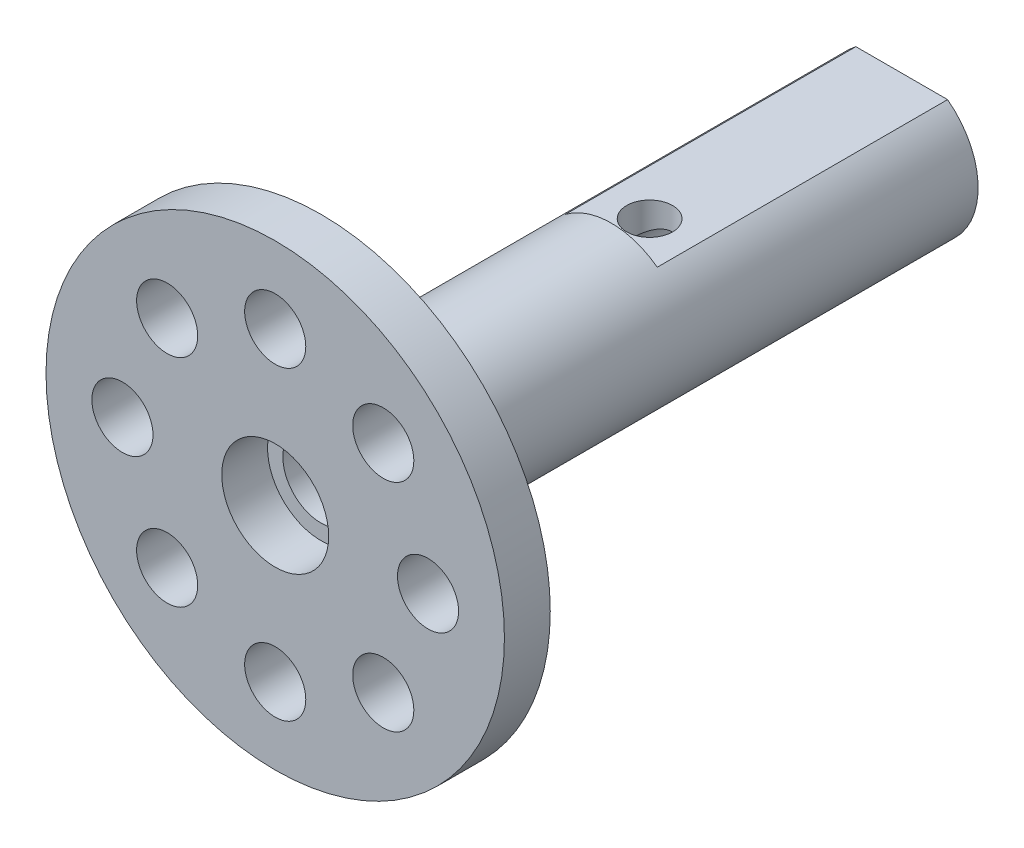
SolidWorks part; units mm, degrees
material "普通碳钢"
ref_plane "前视基准面" through (0, 0, 0) normal (0, 0, 1) x (1, 0, 0)
ref_plane "上视基准面" through (0, 0, 0) normal (0, 1, 0) x (1, 0, 0)
ref_plane "右视基准面" through (0, 0, 0) normal (1, 0, 0) x (0, 0, -1)
sketch "草图1" plane through (0, 0, 0) normal (0, 0, 1) x (1, 0, 0)
  circle A0 centre (0, 0) radius 5
  dimension "D1" = 10
extrude "凸台-拉伸1" add sketch "草图1" along normal blind 35
sketch "草图2" plane through (0, 0, 35) normal (0, 0, 1) x (1, 0, 0)
  circle A0 centre (0, 0) radius 6
  dimension "D1" = 12
extrude "凸台-拉伸2" add sketch "草图2" along normal blind 3
sketch "草图3" plane through (0, 0, 38) normal (0, 0, 1) x (1, 0, 0)
  line L0 (10, 0) -> (0, 0) construction
  line L1 (0, 0) -> (7.0711, 7.0711) construction
  circle A0 centre (0, 0) radius 15
  circle A1 centre (0, 0) radius 10 construction
  circle A2 centre (0, 10) radius 2
  circle A3 centre (10, 0) radius 2
  circle A4 centre (0, -10) radius 2
  circle A5 centre (-10, 0) radius 2
  circle A6 centre (7.0711, 7.0711) radius 2
  circle A7 centre (7.0711, -7.0711) radius 2
  circle A8 centre (-7.0711, -7.0711) radius 2
  circle A9 centre (-7.0711, 7.0711) radius 2
  point P23 (0, 0)
  dimension "D1" = 30
  dimension "D2" = 20
  dimension "D3" = 4
  dimension "D4" = 4
  dimension "D5" = 4
  dimension "D6" = 4
  dimension "D8" = 4
  dimension "D7" = 45
  dimension "D9" = 4
extrude "凸台-拉伸3" add sketch "草图3" along normal blind 3
sketch "草图4" plane through (0, 0, 0) normal (0, 0, -1) x (-1, 0, 0)
  line L0 (-3, 4) -> (3, 4)
  line L1 (-3, -4) -> (3, -4)
  circle A0 centre (0, 0) radius 5 construction
  arc A1 (3, 4) -> (-3, 4) centre (0, 0) ccw
  arc A2 (-3, -4) -> (3, -4) centre (0, 0) ccw
  dimension "D2" = 4
  dimension "D1" = 4
extrude "切除-拉伸1" cut sketch "草图4" against normal blind 19
sketch "草图5" plane through (0, 4, 0) normal (0, 1, 0) x (1, 0, 0)
  line L0 (3, -19) -> (-3, -19) construction
  circle A0 centre (0, -16.5) radius 1.5
  dimension "D1" = 3
  dimension "D2" = 2.5
extrude "切除-拉伸2" cut sketch "草图5" against normal through all
sketch "草图6" plane through (0, 0, 0) normal (0, 0, -1) x (-1, 0, 0)
  circle A0 centre (0, 0) radius 2.5
  dimension "D1" = 5
extrude "切除-拉伸3" cut sketch "草图6" against normal through all
sketch "草图7" plane through (0, 0, 41) normal (0, 0, 1) x (1, 0, 0)
  circle A0 centre (0, 0) radius 3.5
  dimension "D1" = 7
extrude "切除-拉伸4" cut sketch "草图7" against normal blind 3
